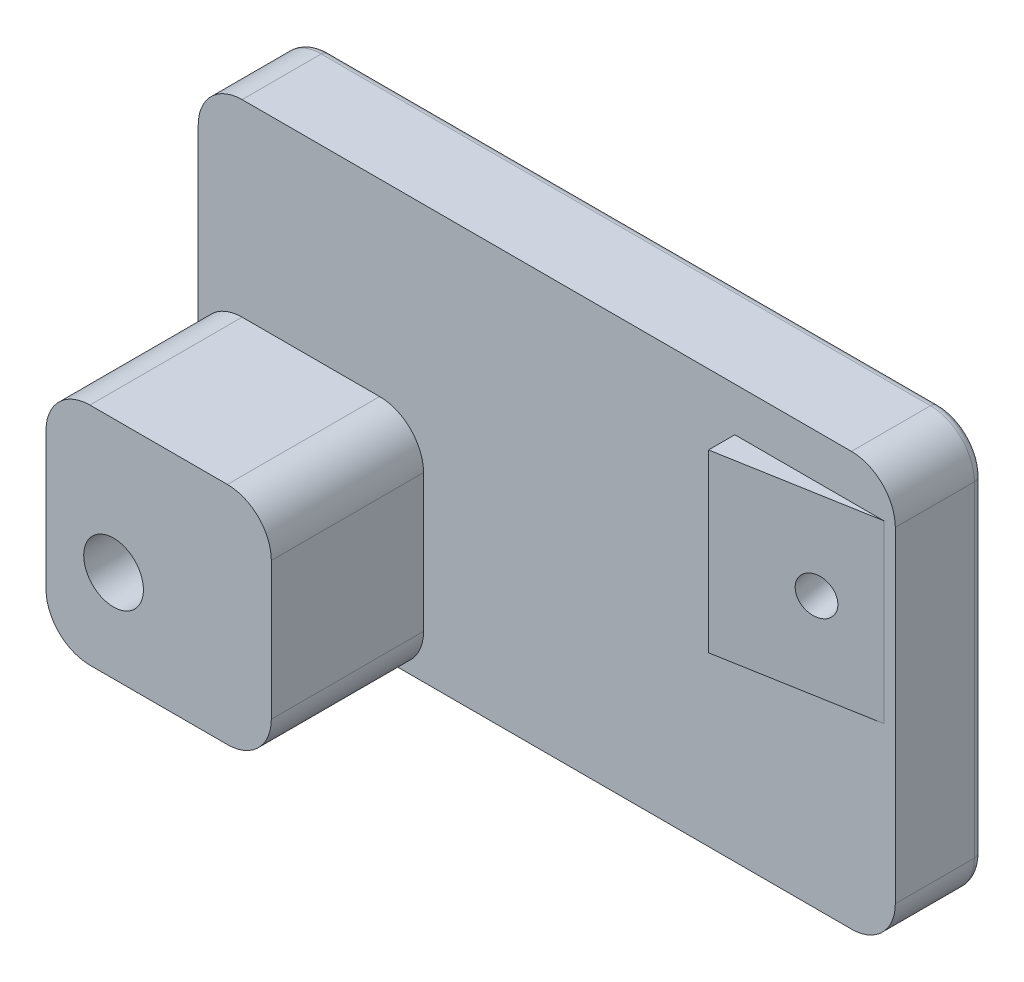
SolidWorks part; units mm, degrees
ref_plane "前视基准面" through (0, 0, 0) normal (0, 0, 1) x (1, 0, 0)
ref_plane "上视基准面" through (0, 0, 0) normal (0, 1, 0) x (1, 0, 0)
ref_plane "右视基准面" through (0, 0, 0) normal (1, 0, 0) x (0, 0, -1)
sketch "Sketch1" plane through (0, 0, 0) normal (0, 0, 1) x (1, 0, 0)
  line L1 (-49.3825, 22.0797) -> (42.9799, 22.0797)
  line L2 (-49.3825, 22.0797) -> (-49.3825, -7.9203)
  line L3 (-49.3825, -7.9203) -> (42.9799, -7.9203)
  line L4 (42.9799, 22.0797) -> (42.9799, -7.9203)
  line L5 (-49.3825, -7.9203) -> (-5.6825, -7.9203)
  line L6 (-49.3825, -7.9203) -> (-49.3825, -41.0233)
  line L7 (-49.3825, -41.0233) -> (-5.6825, -41.0233)
  line L8 (-5.6825, -7.9203) -> (-5.6825, -41.0233)
  circle A0 centre (-31.8099, 6.9927) radius 2.5
  circle A1 centre (33.1901, 6.9927) radius 1
  dimension "D2" = 30
  dimension "D3" = 65
extrude "Boss-Extrude1" add sketch "Sketch1" along normal blind 10 contours L1 L4 L3 L2 | L6 L5 L8 L7
sketch "Sketch4" plane through (0, 0, 0) normal (0, 0, -1) x (-1, 0, 0)
  circle A1 centre (31.8099, 6.9927) radius 2.5
ref_plane "Plane1" through (0, 7.0797, 0) normal (0, -1, 0) x (-1, 0, 0)
sketch "Sketch10" plane through (0, 7.0797, 0) normal (0, -1, 0) x (-1, 0, 0)
  line L0 (-41.6731, 0) -> (-24.7071, 0)
  line L1 (49.3825, 0) -> (-42.9799, 0) construction
  line L2 (-24.7071, 0) -> (-24.7071, 2.9916)
  line L3 (-24.7071, 2.9916) -> (-41.6731, 0)
  line L4 (-42.9799, -5) -> (-13.4546, -5) construction
  line L5 (-42.9799, -10) -> (-42.9799, 0) construction
  line L6 (-24.7071, -10) -> (-24.7071, -12.9916)
  line L7 (-41.6731, -10) -> (-24.7071, -10)
  line L8 (-24.7071, -12.9916) -> (-41.6731, -10)
  dimension "D1" = 10
  dimension "D2" = 8.483
  dimension "D3" = 8.483
sketch "Sketch13" plane through (0, 0, 10) normal (0, 0, 1) x (1, 0, 0)
  line L0 (-49.3825, 22.0797) -> (-49.3825, -41.0233) construction
  line L2 (-49.3825, -41.0233) -> (-5.6825, -41.0233) construction
  circle A0 centre (-28.6925, -14.5433) radius 2.5
  dimension "D3" = 5
  dimension "D1" = 20.69
  dimension "D2" = 26.48
extrude "Boss-Extrude3" add sketch "Sketch10" along normal mid plane 20 contours L6 L8 L7
sketch "Sketch15" plane through (2.9667, 0, 16.825) normal (0.1736, 0, 0.9848) x (0.9848, 0, -0.1736)
  circle A0 centre (32.6859, 6.9927) radius 1
hole_wizard "M5 Tapped Hole1" positions "3DSketch13" profile "Sketch16" tap size "M5" standard "GB" end condition through all
sketch3d "3DSketch13"
  point P0 (35.156, 6.9927, 11.1491)
sketch "Sketch16" plane through (35.156, 6.9927, 11.1491) normal (0, 1, 0) x (0.9848, 0, -0.1736)
  line L0 (0, 0) -> (0, 25.6597)
  line L1 (0, 25.6597) -> (2.1, 25.6597)
  line L2 (2.1, 25.6597) -> (2.1, 0)
  line L5 (2.1, 0) -> (0, 0)
  line L11 (0, -6.35) -> (0, 107.95) construction
  dimension "Thru Tap Drill Dia." = 4.2
  dimension "Thru Tap Drill Depth" = 25.6597
cosmetic thread "Hole Thread3" parameters "D2"=5
sketch "Sketch18" plane through (0, 0, 10) normal (0, 0, 1) x (1, 0, 0)
  line L0 (-49.3825, 22.0797) -> (-49.3825, -41.0233) construction
  line L1 (-49.3825, -25.0233) -> (-5.6825, -25.0233)
  line L2 (-49.3825, -25.0233) -> (-49.3825, -41.0233)
  line L3 (-49.3825, -41.0233) -> (-5.6825, -41.0233)
  line L4 (-5.6825, -25.0233) -> (-5.6825, -41.0233)
  line L6 (-49.3825, 22.0797) -> (-36.3825, 22.0797)
  line L7 (-49.3825, 22.0797) -> (-49.3825, -25.0233)
  line L8 (-49.3825, -25.0233) -> (-36.3825, -25.0233)
  line L9 (-36.3825, 22.0797) -> (-36.3825, -25.0233)
  line M2 (-49.3825, 22.0797) -> (-49.3825, -41.0233)
  line M3 (-49.3825, -41.0233) -> (-5.6825, -41.0233)
  line M4 (-5.6825, -41.0233) -> (-5.6825, -7.9203)
  line M7 (42.9799, 22.0797) -> (-49.3825, 22.0797)
extrude "Cut-Extrude1" cut sketch "Sketch18" against normal blind 10 contours L1 M2 M3 M4 | L9 L1 M7 M2
sketch "Sketch20" plane through (0, 0, 0) normal (0, 0, -1) x (-1, 0, 0)
  line L0 (36.3825, -25.0233) -> (5.6825, -25.0233) construction
  line L1 (5.6825, -7.9203) -> (15.6825, -7.9203)
  line L2 (5.6825, -7.9203) -> (5.6825, -25.0233)
  line L3 (5.6825, -25.0233) -> (15.6825, -25.0233)
  line L4 (15.6825, -7.9203) -> (15.6825, -25.0233)
extrude "Cut-Extrude3" cut sketch "Sketch20" against normal blind 10
sketch "Sketch22" plane through (0, 0, 10) normal (0, 0, 1) x (1, 0, 0)
  line L0 (-36.3825, 22.0797) -> (-36.3825, -25.0233) construction
  line L1 (-15.6825, -25.0233) -> (-36.3825, -25.0233)
  line L2 (-15.6825, -25.0233) -> (-15.6825, -7.9203)
  line L3 (-15.6825, -7.9203) -> (-36.3825, -7.9203)
  line L4 (-36.3825, -25.0233) -> (-36.3825, -7.9203)
  line L5 (-15.6825, -7.9203) -> (42.9799, -7.9203) construction
extrude "Boss-Extrude4" add sketch "Sketch22" along normal blind 17.3288
sketch "Sketch23" plane through (0, 0, 0) normal (0, 0, -1) x (-1, 0, 0)
  line L1 (-42.9799, -7.9203) -> (15.6825, -7.9203)
  line L2 (-42.9799, -7.9203) -> (-42.9799, -25.0233)
  line L3 (-42.9799, -25.0233) -> (15.6825, -25.0233)
  line L4 (15.6825, -7.9203) -> (15.6825, -25.0233)
extrude "Boss-Extrude5" add sketch "Sketch23" along direction (0, 0, 1) on the side against the normal blind 10
sketch "Sketch24" plane through (0, 0, 0) normal (0, 0, -1) x (-1, 0, 0)
  line L0 (36.3825, 22.0797) -> (-42.9799, 22.0797) construction
  line L1 (36.3825, 22.0797) -> (36.3825, -25.0233) construction
  circle A0 centre (28.6925, -14.5403) radius 4
  dimension "D1" = 36.62
  dimension "D2" = 7.69
sketch "Sketch27" plane through (0, 0, 27.3288) normal (0, 0, 1) x (1, 0, 0)
  line L0 (-18.0801, -25.0233) -> (-18.0801, 0.6285) construction
  line L1 (-36.3825, -25.0233) -> (-15.7306, -25.0233)
  line L2 (-36.3825, -25.0233) -> (-36.3825, -4.3715)
  line L3 (-31.3825, 0.6285) -> (-15.7306, 0.6285)
  line L4 (-10.7306, -20.0233) -> (-10.7306, -4.3715)
  line L5 (-36.3825, -6.4227) -> (-10.7306, -6.4227) construction
  arc A0 (-15.7306, -25.0233) -> (-10.7306, -20.0233) centre (-15.7306, -20.0233) ccw
  arc A1 (-36.3825, -4.3715) -> (-31.3825, 0.6285) centre (-31.3825, -4.3715) cw
  arc A2 (-15.7306, 0.6285) -> (-10.7306, -4.3715) centre (-15.7306, -4.3715) cw
  dimension "D1" = 5
extrude "Boss-Extrude6" add sketch "Sketch27" against normal blind 20
hole_wizard "M8 Tapped Hole3" positions "3DSketch16" profile "Sketch29" tap size "M8" standard "GB" end condition through all
sketch3d "3DSketch16"
  point P0 (-28.6925, -14.5403, 0)
sketch "Sketch29" plane through (-28.6925, -14.5403, 0) normal (1, 0, 0) x (0, 1, 0)
  line L0 (0, 0) -> (0, 27.3288)
  line L1 (0, 27.3288) -> (3.4, 27.3288)
  line L2 (3.4, 27.3288) -> (3.4, 0)
  line L5 (3.4, 0) -> (0, 0)
  line L11 (0, -6.35) -> (0, 107.95) construction
  dimension "Thru Tap Drill Dia." = 6.8
  dimension "Thru Tap Drill Depth" = 27.3288
cosmetic thread "Hole Thread7" parameters "D2"=8
fillet "Fillet4" radius 5 1 edges at (-36.3825, -25.0233, 13.6644)
fillet "Fillet6" radius 5 3 edges at (-36.3825, 22.0797, 5) (42.9799, 22.0797, 5) (42.9799, -25.0233, 5)
fillet "Fillet7" radius 1 8 edges at (-34.918, 20.6152, 0) (3.2987, 22.0797, 0) (41.5154, 20.6152, 0) (42.9799, -1.4718, 0) (41.5154, -23.5588, 0) (3.2987, -25.0233, 0) (-34.918, -23.5588, 0) (-36.3825, -1.4718, 0)
